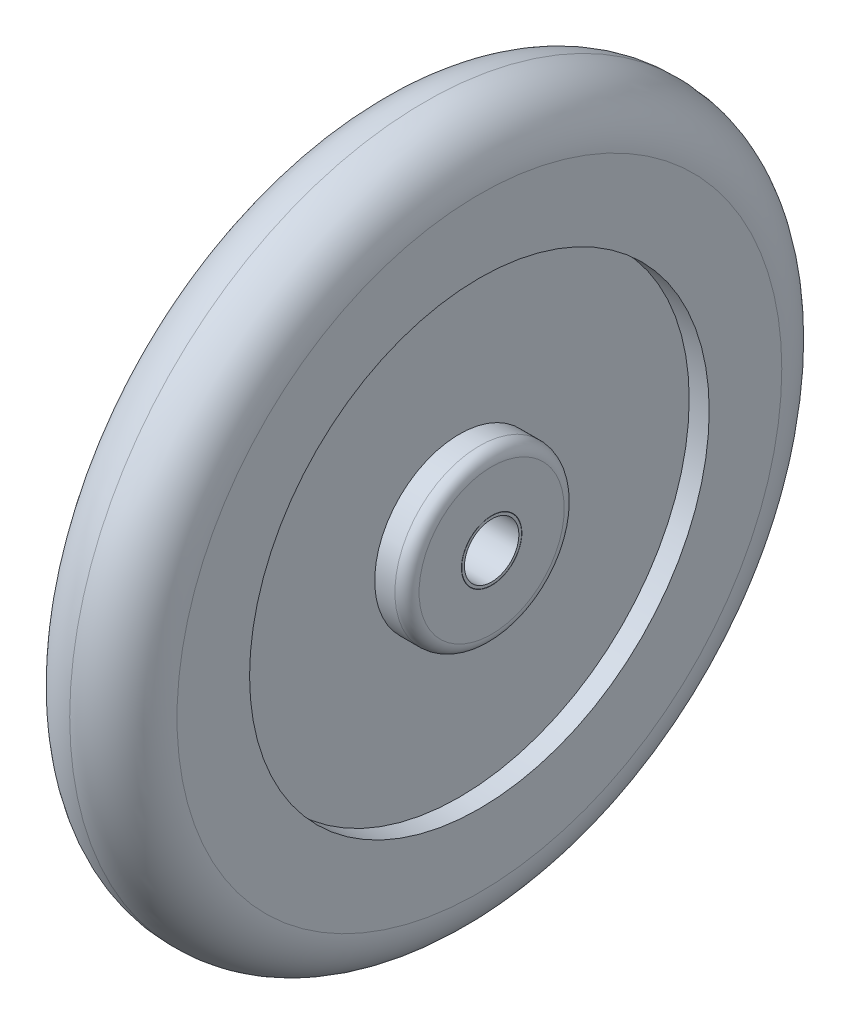
SolidWorks part; units mm, degrees
ref_plane "Front Plane" through (0, 0, 0) normal (0, 0, 1) x (1, 0, 0)
ref_plane "Top Plane" through (0, 0, 0) normal (0, 1, 0) x (1, 0, 0)
ref_plane "Right Plane" through (0, 0, 0) normal (1, 0, 0) x (0, 0, -1)
sketch "Sketch2" plane through (0, 0, 0) normal (0, 0, 1) x (1, 0, 0)
  line L0 (0, 0) -> (-108.0021, 0) construction
  line L1 (-11.0273, 0) -> (-11.0273, 12)
  line L2 (-9.0273, 14) -> (-5.6924, 14)
  line L3 (-5.6924, 14) -> (-5.6924, 35.7925)
  line L4 (0, 58.7386) -> (0, 0)
  line L5 (-5.6924, 35.7925) -> (-5.6924, 38)
  line L6 (-5.6924, 38) -> (-9, 38)
  line L7 (11.0273, 0) -> (-11.0273, 0)
  line L8 (-9, 38) -> (-9, 50)
  line L9 (0, 0) -> (0, 98.8397) construction
  line L10 (9, 38) -> (9, 50)
  line L11 (5.6924, 38) -> (9, 38)
  line L12 (5.6924, 35.7925) -> (5.6924, 38)
  line L13 (5.6924, 14) -> (5.6924, 35.7925)
  line L14 (9.0273, 14) -> (5.6924, 14)
  line L15 (11.0273, 0) -> (11.0273, 12)
  arc A0 (-9, 50) -> (0, 58.7386) centre (-0.2576, 50) cw
  arc A1 (-11.0273, 12) -> (-9.0273, 14) centre (-9.0273, 12) cw
  arc A2 (11.0273, 12) -> (9.0273, 14) centre (9.0273, 12) ccw
  arc A3 (9, 50) -> (0, 58.7386) centre (0.2576, 50) ccw
  dimension "D1" = 50
  dimension "D2" = 2
  dimension "D3" = 12
  dimension "D4" = 12
  dimension "D5" = 18
revolve "Revolve1" add sketch "Sketch2" angle 360 about L0
sketch "Sketch3" plane through (11.0273, 0, 0) normal (1, 0, 0) x (0, 0, -1)
  circle A0 centre (0, 0) radius 5
  circle A1 centre (0, 0) radius 4.5
  circle A2 centre (0, 0) radius 4.95
  dimension "D1" = 10
  dimension "D2" = 9.9
  dimension "D3" = 9
extrude "Cut-Extrude1" cut sketch "Sketch3" against normal through all contours A1 | A0 A2
fillet "Fillet1" radius 1 1 edges at (-5.6924, 0, -38)
fillet "Fillet2" radius 0.2 1 edges at (-9, 0, -38)
